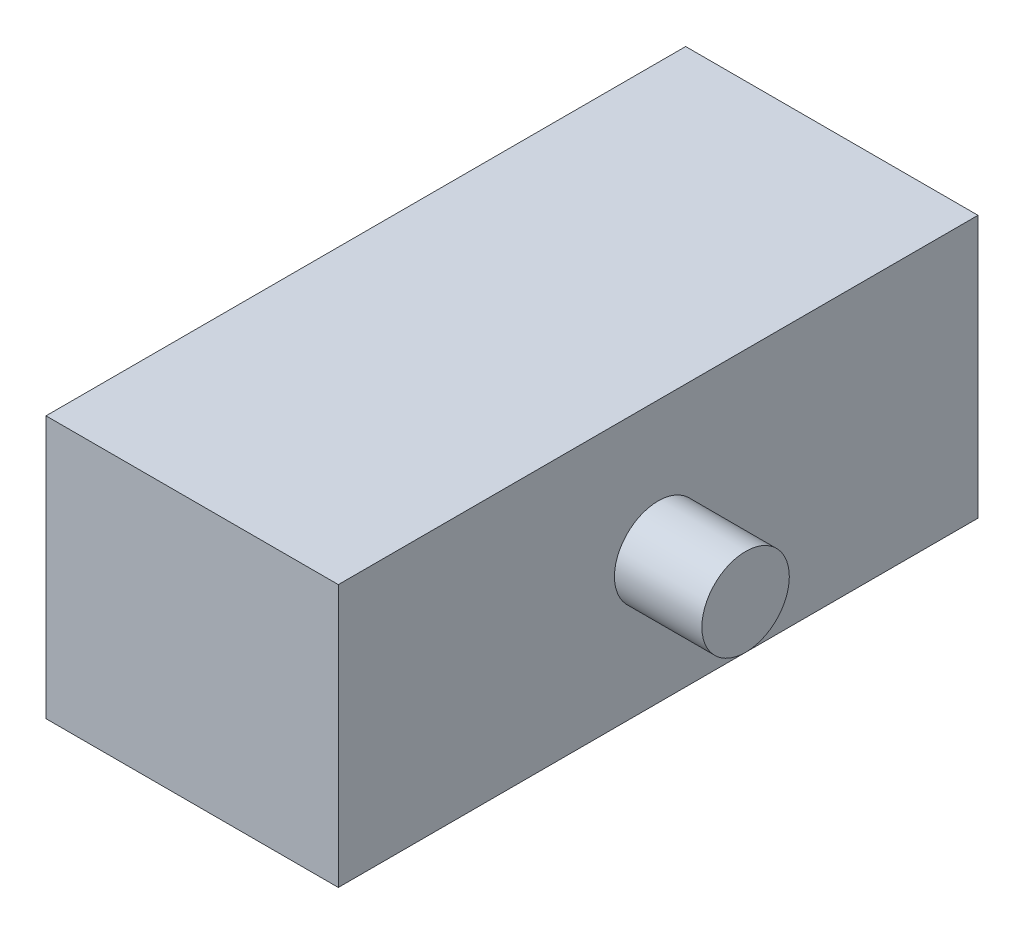
SolidWorks part; units mm, degrees
ref_plane "前视基准面" through (0, 0, 0) normal (0, 0, 1) x (1, 0, 0)
ref_plane "上视基准面" through (0, 0, 0) normal (0, 1, 0) x (1, 0, 0)
ref_plane "右视基准面" through (0, 0, 0) normal (1, 0, 0) x (0, 0, -1)
sketch "草图1" plane through (0, 0, 0) normal (0, 1, 0) x (1, 0, 0)
  line L1 (-8.3584, 18.2892) -> (8.3584, 18.2892)
  line L2 (-8.3584, 18.2892) -> (-8.3584, -18.2892)
  line L3 (-8.3584, -18.2892) -> (8.3584, -18.2892)
  line L4 (8.3584, 18.2892) -> (8.3584, -18.2892)
  line L5 (-8.3584, 18.2892) -> (8.3584, -18.2892) construction
  line L6 (-8.3584, -18.2892) -> (8.3584, 18.2892) construction
  point P0 (0, 0)
extrude "凸台-拉伸1" add sketch "草图1" along normal blind 15
sketch "草图2" plane through (8.3584, 0, 0) normal (1, 0, 0) x (0, 0, -1)
  line L0 (-18.2892, 7.5) -> (18.2892, 7.5) construction
  circle A0 centre (0, 7.5) radius 2.5
  point P3 (0, 0)
  point P4 (0, 0)
  dimension "D1" = 5
extrude "凸台-拉伸2" add sketch "草图2" along normal blind 5
